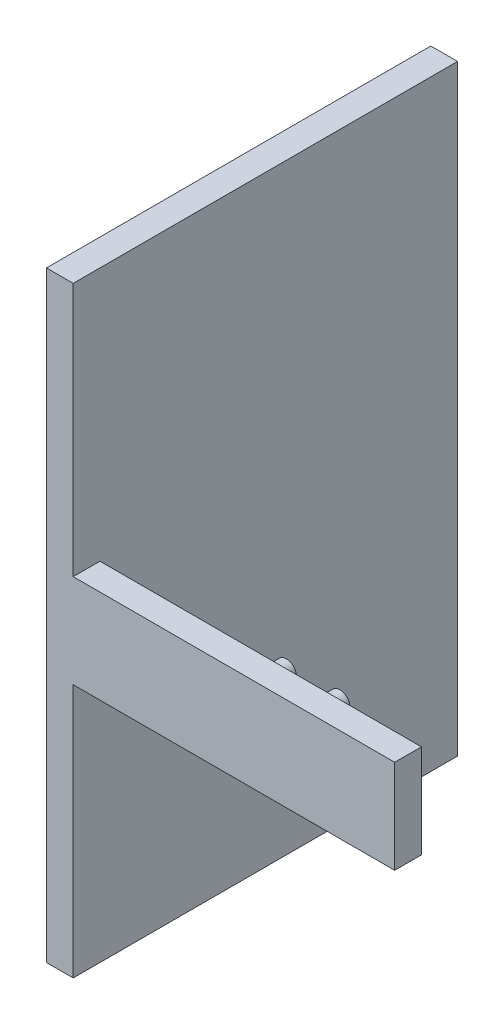
SolidWorks part; units mm, degrees
material "ABS"
ref_plane "Front Plane" through (0, 0, 0) normal (0, 0, 1) x (1, 0, 0)
ref_plane "Top Plane" through (0, 0, 0) normal (0, 1, 0) x (1, 0, 0)
ref_plane "Right Plane" through (0, 0, 0) normal (1, 0, 0) x (0, 0, -1)
ref_plane "P_plate_on_t" through (0, 0, 18.5) normal (0, 0, 1) x (1, 0, 0)
sketch "Sketch1" plane through (0, 0, 18.5) normal (0, 0, 1) x (1, 0, 0)
  line L1 (-126.7, -7) -> (-74.6, -7)
  line L2 (-126.7, -7) -> (-126.7, 7)
  line L3 (-126.7, 7) -> (-74.6, 7)
  line L4 (-74.6, -7) -> (-74.6, 7)
extrude "Boss-Extrude1" add sketch "Sketch1" along normal blind 4
ref_plane "P_torso_shel" through (-126.7, 0, 0) normal (1, 0, 0) x (0, 0, -1)
sketch "Sketch2" plane through (-126.7, 0, 0) normal (1, 0, 0) x (0, 0, -1)
  line L1 (-22.5, -45) -> (35, -45)
  line L2 (-22.5, -45) -> (-22.5, 45)
  line L3 (-22.5, 45) -> (35, 45)
  line L4 (35, -45) -> (35, 45)
extrude "Boss-Extrude2" add sketch "Sketch2" along normal blind 4
ref_plane "Z+15_70" through (0, 0, 15.7) normal (0, 0, 1) x (1, 0, 0)
sketch "Sketch3" plane through (0, 0, 15.7) normal (0, 0, 1) x (1, 0, 0)
  circle A0 centre (-89.6, 4) radius 1.5
  circle A1 centre (-89.6, -4) radius 1.5
  circle A2 centre (-97.6, 4) radius 1.5
  circle A3 centre (-97.6, -4) radius 1.5
extrude "Boss-Extrude3" add sketch "Sketch3" along normal blind 2.8
ref_plane "X-129_50" through (-129.5, 0, 0) normal (1, 0, 0) x (0, 0, -1)
sketch "Sketch4" plane through (-129.5, 0, 0) normal (1, 0, 0) x (0, 0, -1)
  circle A0 centre (15, -30) radius 1.5
  circle A1 centre (-15, -30) radius 1.5
  circle A2 centre (15, 30) radius 1.5
  circle A3 centre (-15, 30) radius 1.5
extrude "Boss-Extrude4" add sketch "Sketch4" along normal blind 2.8
